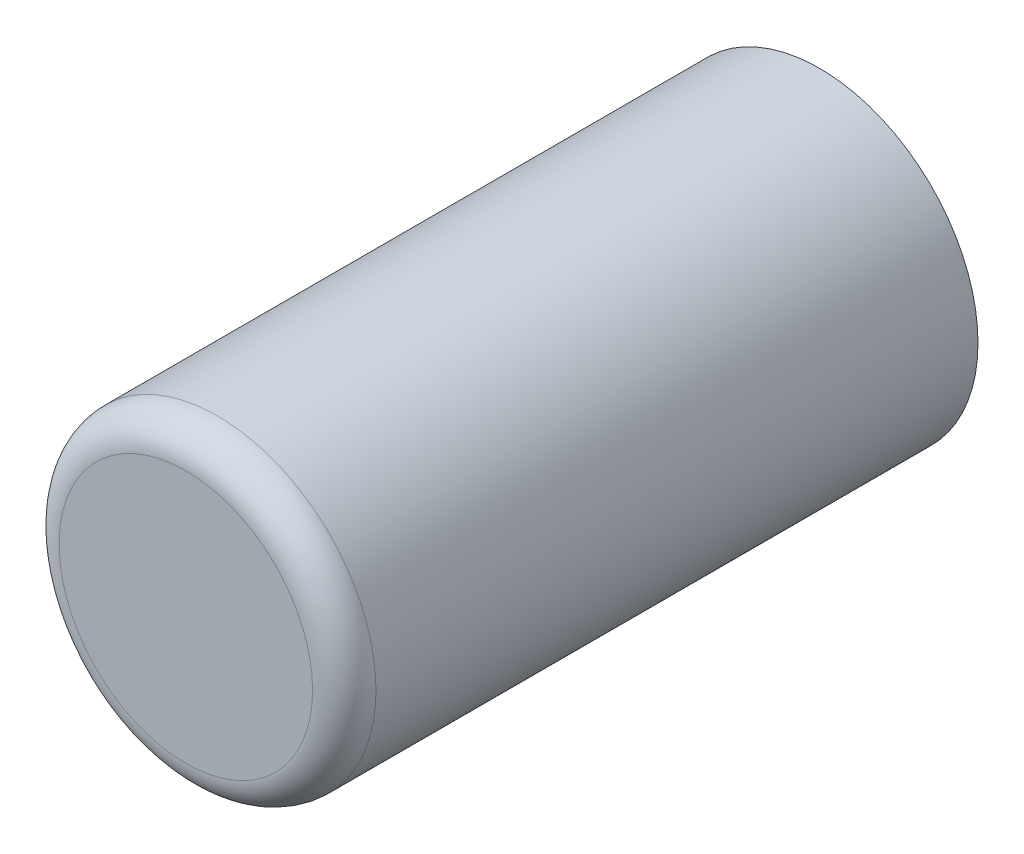
SolidWorks part; units mm, degrees
ref_plane "Спереди" through (0, 0, 0) normal (0, 0, 1) x (1, 0, 0)
ref_plane "Сверху" through (0, 0, 0) normal (0, 1, 0) x (1, 0, 0)
ref_plane "Справа" through (0, 0, 0) normal (1, 0, 0) x (0, 0, -1)
sketch "Эскиз1" plane through (0, 0, 0) normal (0, 0, 1) x (1, 0, 0)
  circle A0 centre (0, 0) radius 25
  dimension "D1" = 50
extrude "Бобышка-Вытянуть1" add sketch "Эскиз1" along normal blind 100
fillet "Скругление1" radius 5 1 edges at (25, 0, 100)
